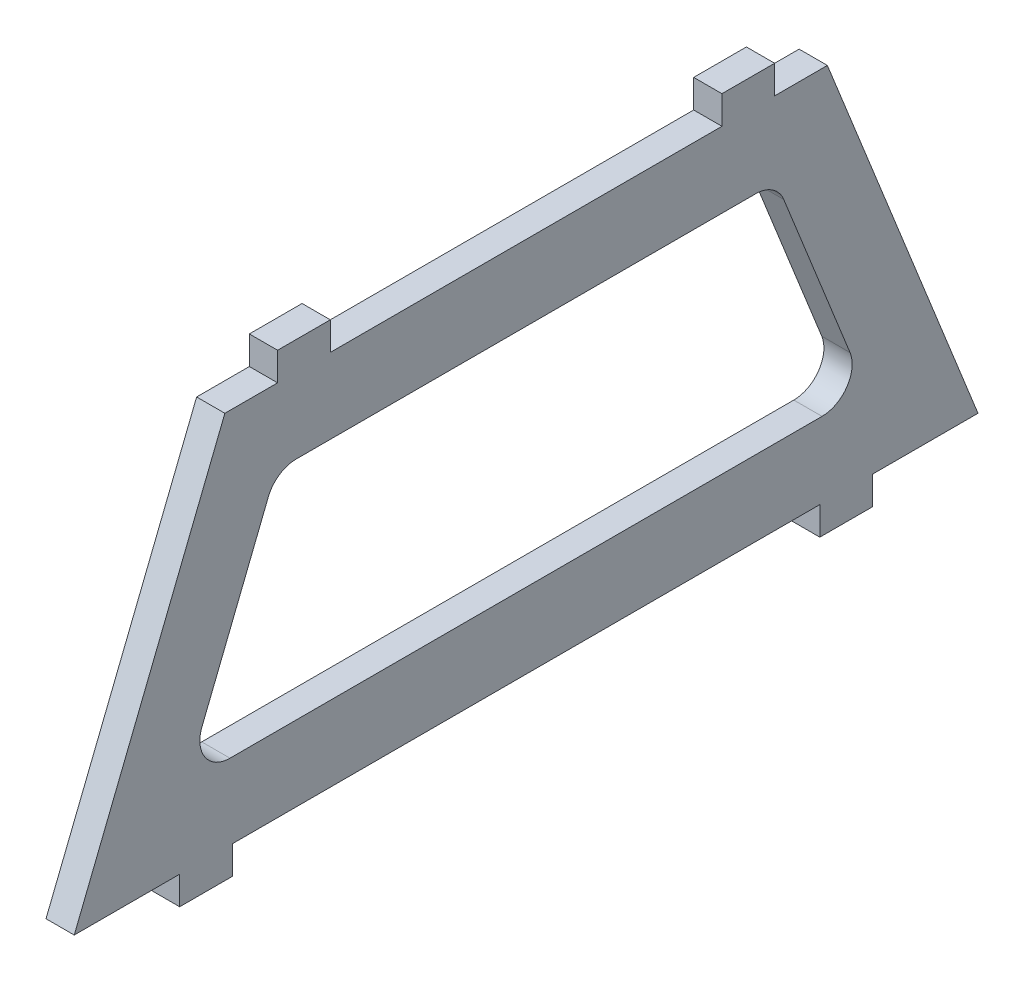
SolidWorks part; units mm, degrees
ref_plane "Front Plane" through (0, 0, 0) normal (0, 0, 1) x (1, 0, 0)
ref_plane "Top Plane" through (0, 0, 0) normal (0, 1, 0) x (1, 0, 0)
ref_plane "Right Plane" through (0, 0, 0) normal (1, 0, 0) x (0, 0, -1)
sketch "Sketch1" plane through (0, 0, 0) normal (1, 0, 0) x (0, 0, -1)
  line L0 (-101.6, 63.5) -> (-127, 0)
  line L1 (0, 0) -> (-101.6, 0)
  line L3 (0, 63.5) -> (-101.6, 63.5)
  line L5 (-127, 0) -> (-101.6, 0)
  line L6 (-50.8, 63.5) -> (-50.8, 52.984) construction
  line L7 (25.4, 0) -> (0, 0)
  line L8 (0, 63.5) -> (25.4, 0)
  line L9 (7.62, -4.7625) -> (-1.27, -4.7625)
  line L10 (-92.71, 63.5) -> (-83.82, 63.5)
  line L11 (-92.71, 63.5) -> (-92.71, 68.2625)
  line L12 (-92.71, 68.2625) -> (-83.82, 68.2625)
  line L13 (-83.82, 63.5) -> (-83.82, 68.2625)
  line L14 (-109.22, 0) -> (-100.33, 0)
  line L15 (-109.22, 0) -> (-109.22, -4.7625)
  line L16 (-109.22, -4.7625) -> (-100.33, -4.7625)
  line L17 (-100.33, 0) -> (-100.33, -4.7625)
  line L18 (-1.27, 0) -> (-1.27, -4.7625)
  line L19 (7.62, 0) -> (-1.27, 0)
  line L20 (7.62, 0) -> (7.62, -4.7625)
  line L21 (-8.89, 68.2625) -> (-17.78, 68.2625)
  line L22 (-17.78, 63.5) -> (-17.78, 68.2625)
  line L23 (-8.89, 63.5) -> (-17.78, 63.5)
  line L24 (-8.89, 63.5) -> (-8.89, 68.2625)
  dimension "D1" = 101.6
  dimension "D2" = 63.5
  dimension "D3" = 25.4
  dimension "D4" = 8.89
  dimension "D5" = 8.89
  dimension "D6" = 4.7625
  dimension "D7" = 17.78
  dimension "D8" = 4.7625
  dimension "D9" = 8.89
extrude "Boss-Extrude1" add sketch "Sketch1" along normal blind 4.7625
sketch "Sketch2" plane through (4.7625, 0, 0) normal (1, 0, 0) x (0, 0, -1)
  line L7 (-17.78, 63.5) -> (-83.82, 63.5) construction
  line L8 (-93.0017, 50.8) -> (-8.636, 50.8)
  line L9 (-93.0017, 50.8) -> (-93.0017, 12.7)
  line L10 (-93.0017, 12.7) -> (-8.636, 12.7)
  line L11 (-8.636, 50.8) -> (-8.636, 12.7)
  line L12 (2.6194, 0) -> (-2.6194, 0) construction
  line L13 (-93.0017, 50.8) -> (-108.2417, 12.7)
  line L14 (-108.2417, 12.7) -> (-93.0017, 12.7)
  line L15 (-101.6, 63.5) -> (-127, 0) construction
  line L16 (0, 2.6194) -> (0, -2.6194) construction
  line L17 (-50.8188, 50.8) -> (-50.8188, 44.4795) construction
  line L18 (6.604, 12.7) -> (-8.636, 12.7)
  line L19 (-8.636, 50.8) -> (6.604, 12.7)
  dimension "D1" = 12.7
  dimension "D2" = 12.7
  dimension "D3" = 12.7
  dimension "D4" = 8.636
extrude "Cut-Extrude1" cut sketch "Sketch2" against normal blind 4.7625
fillet "Fillet1" radius 5.08 4 edges at (2.3813, 12.7, 108.2417) (2.3813, 12.7, -6.604) (2.3813, 50.8, 8.636) (2.3813, 50.8, 93.0017)
